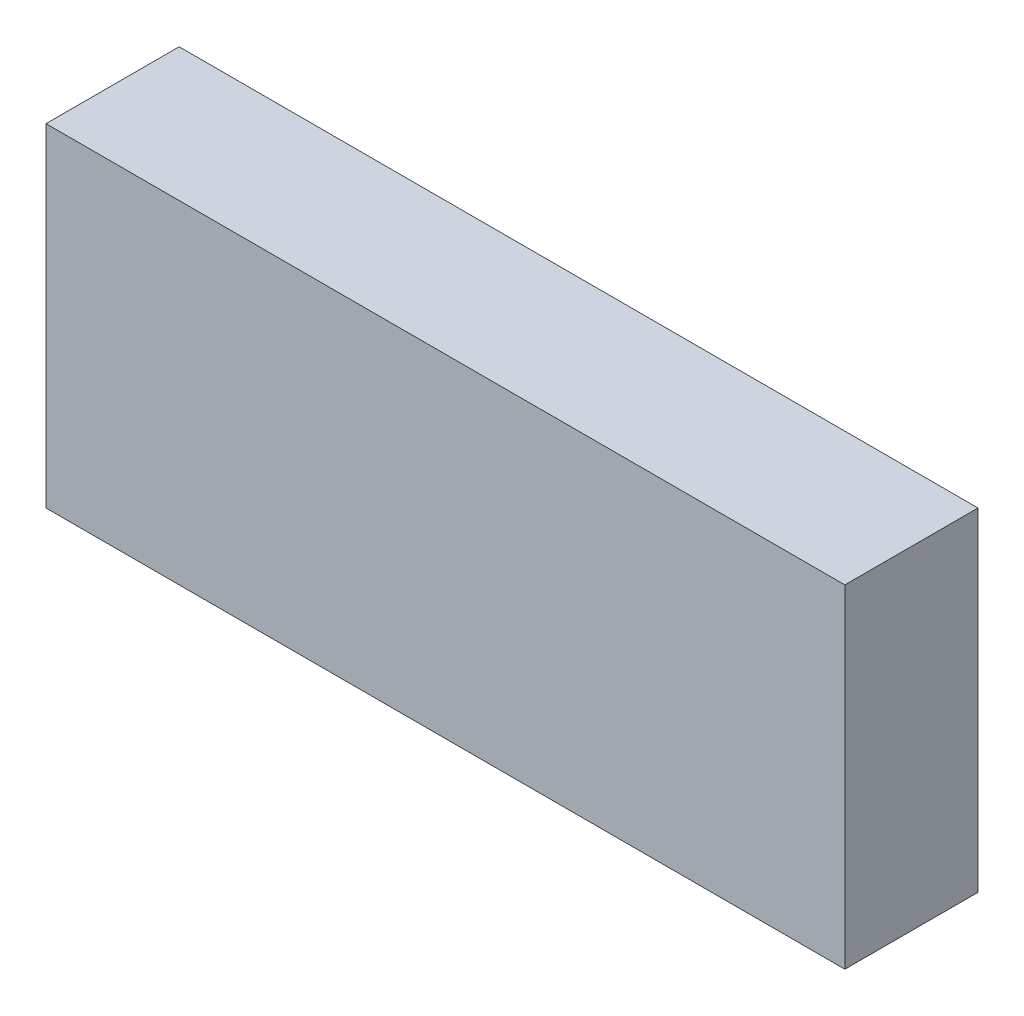
SolidWorks part; units mm, degrees
ref_plane "Front Plane" through (0, 0, 0) normal (0, 0, 1) x (1, 0, 0)
ref_plane "Top Plane" through (0, 0, 0) normal (0, 1, 0) x (1, 0, 0)
ref_plane "Right Plane" through (0, 0, 0) normal (1, 0, 0) x (0, 0, -1)
sketch "Sketch1" plane through (0, 0, 0) normal (0, 0, 1) x (1, 0, 0)
  line L1 (60, 25) -> (-60, 25)
  line L2 (60, 25) -> (60, -25)
  line L3 (60, -25) -> (-60, -25)
  line L4 (-60, 25) -> (-60, -25)
  line L5 (0, -25) -> (0, 25) construction
  line L6 (60, 0) -> (-60, 0) construction
  point P0 (0, 0)
  dimension "D1" = 120
  dimension "D2" = 50
extrude "Boss-Extrude1" add sketch "Sketch1" along normal blind 20
